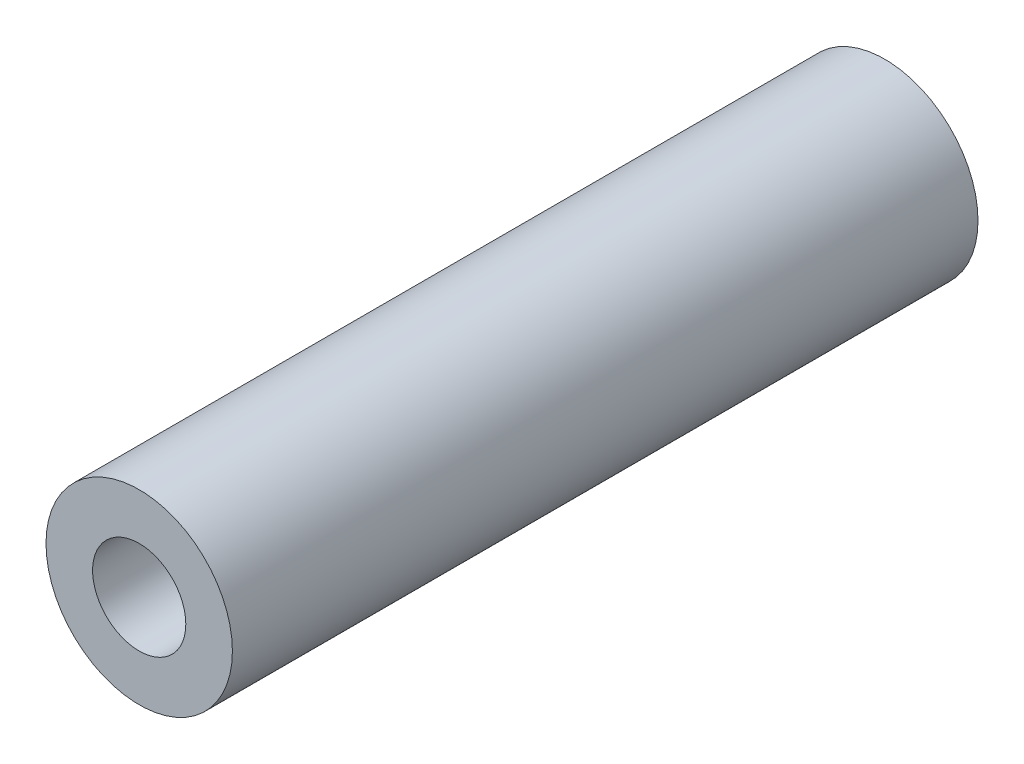
SolidWorks part; units mm, degrees
ref_plane "Front Plane" through (0, 0, 0) normal (0, 0, 1) x (1, 0, 0)
ref_plane "Top Plane" through (0, 0, 0) normal (0, 1, 0) x (1, 0, 0)
ref_plane "Right Plane" through (0, 0, 0) normal (1, 0, 0) x (0, 0, -1)
sketch "Sketch1" plane through (0, 0, 0) normal (0, 0, 1) x (1, 0, 0)
  circle A0 centre (184.2676, 120.1192) radius 2.5
  circle A1 centre (184.2676, 120.1192) radius 1.25
  dimension "D1" = 2.5
  dimension "D2" = 5
extrude "Boss-Extrude1" add sketch "Sketch1" along normal blind 20
